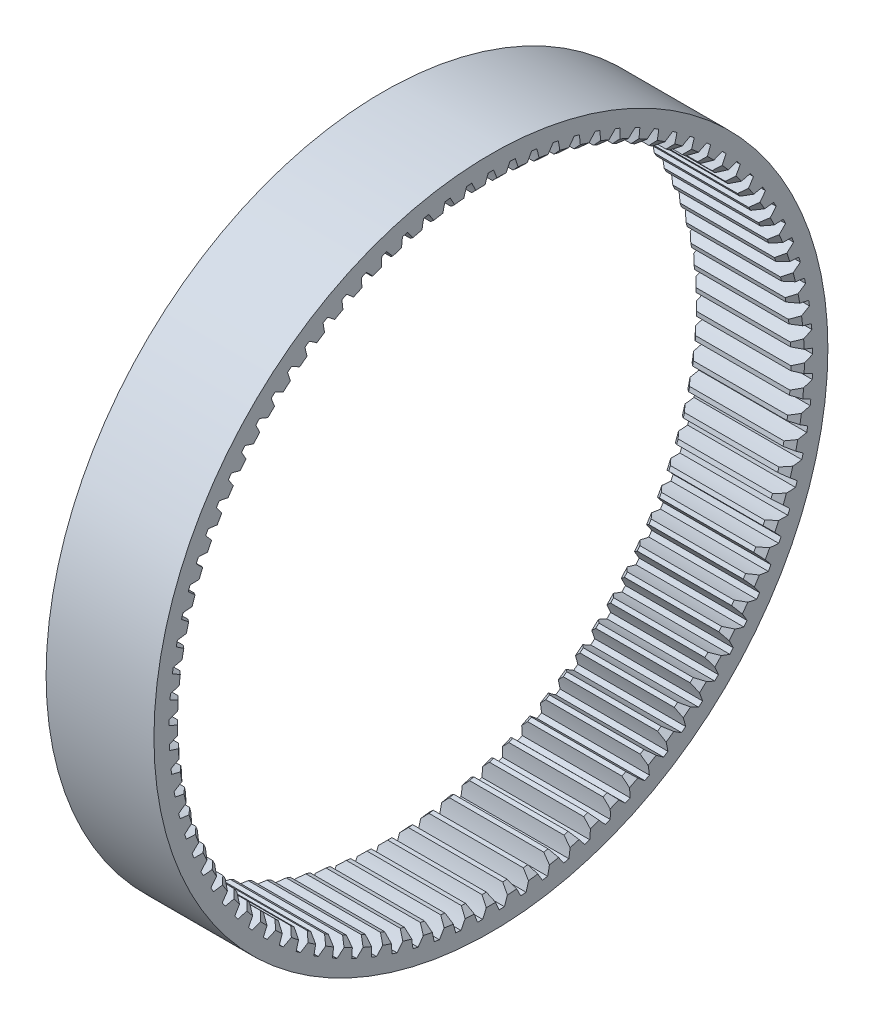
SolidWorks part; units mm, degrees
ref_plane "Plane1" through (0, 0, 0) normal (0, 0, 1) x (1, 0, 0)
ref_plane "Plane2" through (0, 0, 0) normal (0, 1, 0) x (1, 0, 0)
ref_plane "Plane3" through (0, 0, 0) normal (1, 0, 0) x (0, 0, -1)
sketch "HoldingSke" plane through (0, 0, 0) normal (0, 1, 0) x (1, 0, 0)
  line L0 (0, 0) -> (-0.1047, -1.9973)
  line L1 (-15, 0) -> (100, 0) construction
  line L2 (0, 0) -> (-2.1039, 2.3779)
  line L3 (0, 0) -> (-11.863, 4.5341)
  line L4 (0, 0) -> (-0.452, 8.6242)
  line L5 (0, 0) -> (-23.7986, -8.8762)
  line L6 (0, 0) -> (-10.5278, -7.1032)
  line L7 (-2.1039, 2.3779) -> (3.3635, 27.1825)
  line L8 (-76.2, 2.8779) -> (-54.61, 2.8779)
  line L9 (-71.009, 38.7566) -> (-53.1078, 45.2721)
  line L10 (-76.2, 71.12) -> (104.1128, 71.12)
  line L11 (0, 0) -> (-8, 0)
  line L12 (-76.2, 101.6) -> (-76.181, 101.6)
  line L13 (24.9733, 27.94) -> (52.9518, 28.4284)
  line L14 (24.9733, 27.94) -> (24.9743, 27.94)
  line L15 (24.9733, 27.94) -> (100.4006, 29.5858)
  circle A0 centre (0, 0) radius 25
  circle A1 centre (0, 0) radius 12.7
  circle A2 centre (0, 0) radius 12.7
  dimension "MHD" = 25.4
  dimension "Hub_dia" = 25.4
  dimension "Diameter" = 50
  dimension "Num_teeth" = 93
  dimension "Pitch" = 2
  dimension "Overall_len" = 25.4
  dimension "Show_teeth" = 93
  dimension "Thickness" = 12.7
  dimension "OAL" = 25.4001
  dimension "T_dim" = 21.59
  dimension "Ap" = 20
  dimension "H" = 19.05
  dimension "Pitch_radius" = 180.3128
  dimension "Width" = 8
  dimension "Backlash" = 0.019
  dimension "Addendum_fac" = 1
  dimension "Dedendum_fac" = 1.25
  dimension "Clearance_fac" = 0.25
  dimension "Dedendum_add" = 0.001
  dimension "Module" = 0.5
sketch "BasProSke" plane through (0, 0, 0) normal (0, 1, 0) x (1, 0, 0)
  line L0 (-10, 0) -> (60, 0) construction
  line L1 (0, 22.75) -> (0, 25)
  line L2 (0, 22.75) -> (8, 22.75)
  line L3 (8, 22.75) -> (8, 25)
  line L4 (8, 25) -> (0, 25)
  dimension "Diameter" = 50
  dimension "Thickness" = 8
  dimension "Inside_diameter" = 45.5
revolve "Base-Revolve" add sketch "BasProSke" angle 360 about L0
sketch "TooCutSke" plane through (0, 0, 0) normal (1, 0, 0) x (0, 0, -1)
  line L3 (0.4402, 23.2458) -> (0.4402, 53.6633) construction
  line L4 (0, 0) -> (0, 59.563) construction
  line L5 (0, 0) -> (-2.3077, 68.2885) construction
  line L6 (-10.5017, 19.3194) -> (37.1571, 20.93) construction
  circle A0 centre (0, 0) radius 23.25 construction
  circle A1 centre (0, 0) radius 23.876 construction
  circle A2 centre (0, 0) radius 19.6631 construction
  circle A3 centre (0, 0) radius 22.7246 construction
  arc A4 (0.616, 22.7162) -> (0.1934, 23.8752) centre (-10.5017, 19.3194) ccw
  arc A5 (0.616, 22.7162) -> (-0.616, 22.7162) centre (0, 0) ccw
  arc A6 (0.1934, 23.8752) -> (-0.1934, 23.8752) centre (0, 0) ccw
  arc A7 (-0.1934, 23.8752) -> (-0.616, 22.7162) centre (10.5017, 19.3194) ccw
  dimension "Pitch_dia" = 46.5
  dimension "Base_dia" = 39.3261
  dimension "Root_dia" = 47.752
  dimension "Overcut_dia" = 45.4492
  dimension "Flank_rad" = 11.625
  dimension "Half_ang" = 1.935
  dimension "Half_CT" = 0.4402
extrude "ToothCut" cut sketch "TooCutSke" along normal through all
fillet "Breaks" [suppressed] radius 0.05
fillet "RootFillets" [suppressed] radius 0.126
pattern_circular "TeethCuts" count 93 every 3.871 about axis through (-10, 0, 0) along (1, 0, 0) of "RootFillets", "Breaks", "ToothCut"
sketch "Sketch2" plane through (0, 0, 0) normal (0, 0, 1) x (1, 0, 0)
  line L10 (8, -23.25) -> (7.5, -22.75)
  line L11 (7.5, -22.75) -> (8, -22.75)
  line L12 (8, -22.75) -> (8, -23.25)
  line L15 (4, -25) -> (4, -28.4065) construction
  line L16 (0, -25) -> (8, -25) construction
  line L17 (0, -22.75) -> (0, -23.25)
  line L18 (0.5, -22.75) -> (0, -22.75)
  line L19 (0, -23.25) -> (0.5, -22.75)
  line L20 (0, 0) -> (-10.3524, 0) construction
  dimension "D1" = 0.5
revolve "Cut-Revolve1" cut sketch "Sketch2" angle 360 about L20
equation "' \"Module@HoldingSke\" = 6.35"
equation "' \"Num_teeth@HoldingSke\" = 24"
equation "' \"Ap@HoldingSke\" =  14.5"
equation "' \"Ap@HoldingSke\" = 14.5"
equation "' \"Width@HoldingSke\" = 12"
equation "' \"Diameter@HoldingSke\" = 8 * 25.4"
equation "' \"Show_teeth@HoldingSke\" = 100"
equation "' \"Backlash@HoldingSke\" = 0.009 * 25.4"
equation "' \"Addendum_fac@HoldingSke\" = 1.0"
equation "' \"Dedendum_fac@HoldingSke\" = 1.25"
equation "' \"Dedendum_add@HoldingSke\" = 0.00005 * 25.4"
equation "' \"Clearance_fac@HoldingSke\" = 0.25"
equation "\"Pitch@HoldingSke\" = 1 / \"Module@HoldingSke\" "
equation "\"Overcut_dia@TooCutSke\" = (\"Num_teeth@HoldingSke\" - 2 * \"Addendum_fac@HoldingSke\") / \"Pitch@HoldingSke\" - 0.002 * 25.4"
equation "\"Pitch_dia@TooCutSke\" = \"Num_teeth@HoldingSke\" / \"Pitch@HoldingSke\""
equation "\"Base_dia@TooCutSke\" = \"Num_teeth@HoldingSke\" / \"Pitch@HoldingSke\" * cos((\"Ap@HoldingSke\"  * 3.14159265 / 180)) * 0.90"
equation "\"Root_dia@TooCutSke\" = \"Num_teeth@HoldingSke\"  / \"Pitch@HoldingSke\" + 2 *  \"Dedendum_fac@HoldingSke\"/ \"Pitch@HoldingSke\" + \"Dedendum_add@HoldingSke\" * 2"
equation "\"Half_ang@TooCutSke\" = 180 / \"Num_teeth@HoldingSke\""
equation "\"Half_CT@TooCutSke\" = \"Num_teeth@HoldingSke\" / \"Pitch@HoldingSke\" * sin((3.14159265 / 2 / \"Num_teeth@HoldingSke\")) / 2 + 10 * \"Backlash@HoldingSke\" / 4"
equation "\"Flank_rad@TooCutSke\" = \"Num_teeth@HoldingSke\" / \"Pitch@HoldingSke\" / 4"
equation "\"Radius@RootFillets\"= \"Clearance_fac@HoldingSke\" / \"Pitch@HoldingSke\" + \"Dedendum_add@HoldingSke\""
equation "\"Break_rad@Breaks\" = 0.02 / \"Pitch@HoldingSke\" * 5"
equation "\"Num_teeth@TeethCuts\" = int( \"Show_teeth@HoldingSke\" ) + 1"
equation "\"Num_teeth@TeethCuts\" = ((sgn( \"Num_teeth@TeethCuts\" - \"Num_teeth@HoldingSke\" )-1)*( \"Num_teeth@TeethCuts\" - \"Num_teeth@HoldingSke\" ))/-2+ \"Num_teeth@HoldingSke\""
equation "\"Num_teeth@TeethCuts\" = ((sgn( \"Num_teeth@TeethCuts\" - 2.0)+1)*( \"Num_teeth@TeethCuts\" - 2.0))/2 +2.0"
equation "\"Angle@TeethCuts\" = 360.0 / \"Num_teeth@HoldingSke\""
equation "\"Diameter@BasProSke\" = \"Num_teeth@HoldingSke\"  / \"Pitch@HoldingSke\" + 2 *  \"Dedendum_fac@HoldingSke\"/ \"Pitch@HoldingSke\" + \"Dedendum_add@HoldingSke\" * 2 + 0.002 * 25.4"
equation "\"Diameter@BasProSke\" = ((sgn( \"Diameter@BasProSke\"  - \"Diameter@HoldingSke\" )+1)*( \"Diameter@BasProSke\"  - \"Diameter@HoldingSke\" ))/2 + \"Diameter@HoldingSke\""
equation "\"Inside_diameter@BasProSke\" =  (\"Num_teeth@HoldingSke\" - 2 * \"Addendum_fac@HoldingSke\") / \"Pitch@HoldingSke\" "
equation "\"Thickness@BasProSke\"  = \"Width@HoldingSke\""
